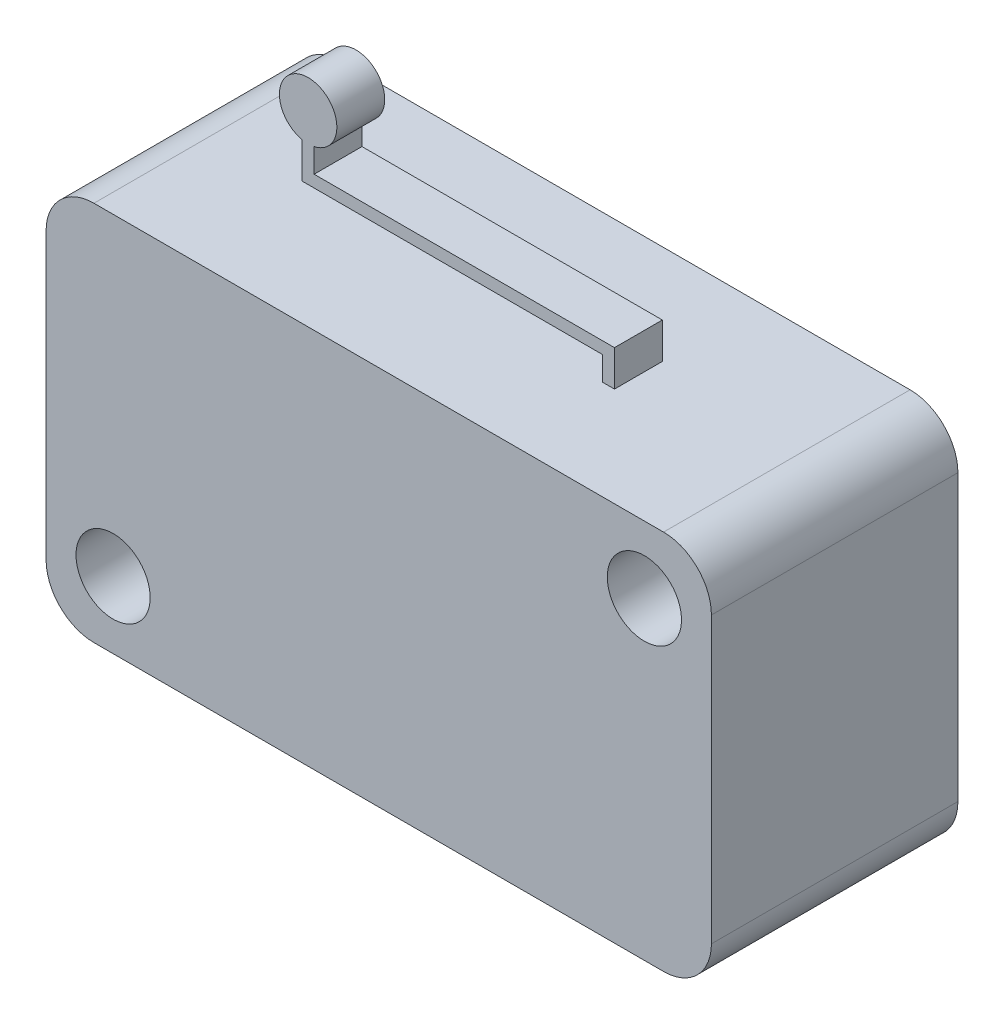
SolidWorks part; units mm, degrees
ref_plane "Front Plane" through (0, 0, 0) normal (0, 0, 1) x (1, 0, 0)
ref_plane "Top Plane" through (0, 0, 0) normal (0, 1, 0) x (1, 0, 0)
ref_plane "Right Plane" through (0, 0, 0) normal (1, 0, 0) x (0, 0, -1)
sketch "Sketch1" plane through (0, 0, 0) normal (0, 0, 1) x (1, 0, 0)
  line L0 (2.8, 2.8) -> (25, 2.8) construction
  line L1 (2, 0) -> (25.8, 0)
  line L2 (0, 2) -> (0, 13.9)
  line L3 (2, 15.9) -> (25.8, 15.9)
  line L4 (27.8, 2) -> (27.8, 13.9)
  line L5 (25, 2.8) -> (25, 13.1) construction
  line L6 (25, 13.1) -> (2.8, 13.1) construction
  line L7 (2.8, 13.1) -> (2.8, 2.8) construction
  arc A0 (2, 0) -> (0, 2) centre (2, 2) cw
  arc A1 (27.8, 2) -> (25.8, 0) centre (25.8, 2) cw
  arc A2 (27.8, 13.9) -> (25.8, 15.9) centre (25.8, 13.9) ccw
  arc A3 (2, 15.9) -> (0, 13.9) centre (2, 13.9) ccw
  circle A4 centre (2.8, 2.8) radius 1.55
  circle A5 centre (25, 13.1) radius 1.55
  point P7 (0, 0)
  point P10 (27.8, 0)
  point P15 (0, 15.9)
  point P20 (13.9, 2.8)
  point P23 (13.9, 0)
  point P24 (25, 7.95)
  point P25 (27.8, 7.95)
  dimension "D3" = 2
  dimension "D5" = 3.1
  dimension "D1" = 27.8
  dimension "D2" = 15.9
  dimension "D4" = 22.2
  dimension "D6" = 10.3
extrude "Boss-Extrude1" add sketch "Sketch1" along normal blind 10.3
ref_plane "Plane1" through (0, 0, 5.15) normal (0, 0, 1) x (1, 0, 0)
sketch "Sketch2" plane through (0, 0, 5.15) normal (0, 0, 1) x (1, 0, 0)
  line L0 (6.55, 18.4) -> (6.55, 16.9)
  line L2 (6.55, 16.9) -> (7.05, 16.9)
  line L3 (7.05, 18.4) -> (7.05, 17.4)
  line L4 (7.05, 16.9) -> (19.1, 16.9)
  line L6 (19.6, 17.4) -> (7.05, 17.4)
  line L7 (19.1, 16.9) -> (19.1, 15.9)
  line L8 (19.1, 15.9) -> (19.6, 15.9)
  line L9 (19.6, 15.9) -> (19.6, 17.4)
  line L11 (25.8, 15.9) -> (2, 15.9) construction
  line L12 (6.55, 17.65) -> (7.05, 17.65) construction
  line L13 (27.8, 2) -> (27.8, 13.9) construction
  arc A0 (7.05, 18.4) -> (6.55, 18.4) centre (6.8, 19.5737) ccw
  point P11 (6.8, 17.65)
  point P13 (6.8, 16.9)
  dimension "D1" = 2.4
  dimension "D2" = 0.5
  dimension "D3" = 0.5
  dimension "D4" = 0.5
  dimension "D5" = 12.8
  dimension "D6" = 8.2
  dimension "D7" = 1
  dimension "D8" = 1.5
extrude "Boss-Extrude2" add sketch "Sketch2" along normal blind 1 and the other way blind 1
